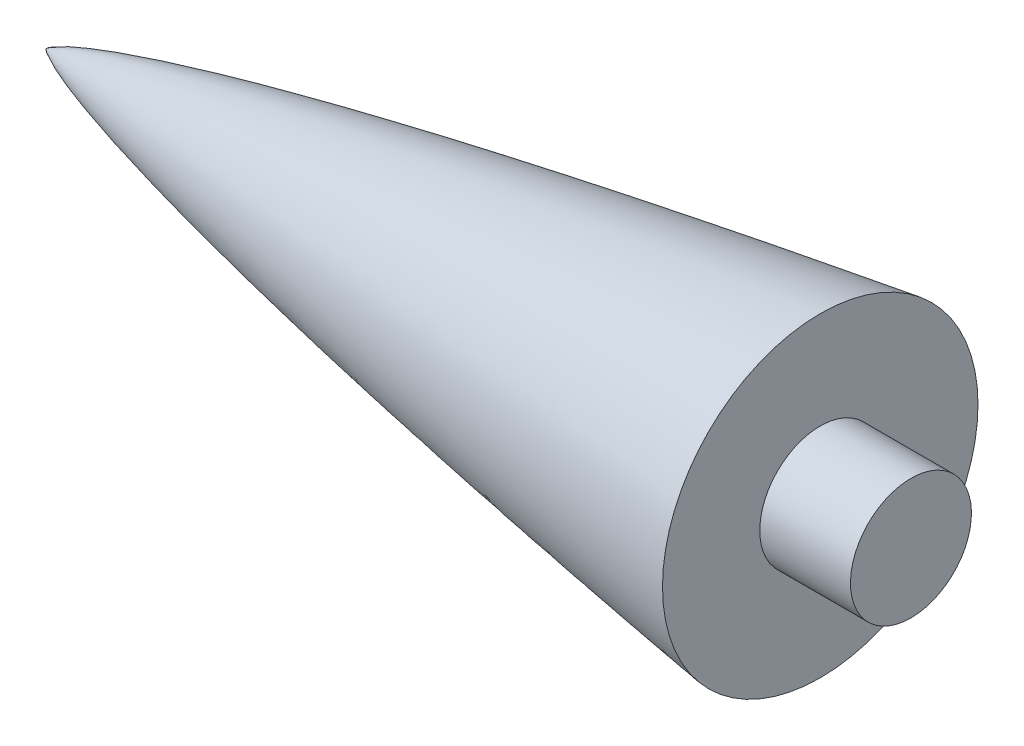
SolidWorks part; units mm, degrees
material "6061-T6 (SS)"
ref_plane "Front" through (0, 0, 0) normal (0, 0, 1) x (1, 0, 0)
ref_plane "Top" through (0, 0, 0) normal (0, 1, 0) x (1, 0, 0)
ref_plane "Right" through (0, 0, 0) normal (1, 0, 0) x (0, 0, -1)
sketch "Sketch7" plane through (0, 0, 0) normal (0, 0, 1) x (1, 0, 0)
  line L0 (0, 0) -> (1126.623, 0) construction
  line L1 (762, 83.8413) -> (762, 0)
  line L2 (0, 0) -> (762, 0)
  spline S0 degree 4 poles (0, 0) (0.0025, 0.0077) (0.0085, 0.0225) (0.0254, 0.0499) (0.0657, 0.1001) (0.1275, 0.1632) (0.2121, 0.2373) (0.3323, 0.3316) (0.4768, 0.4341) (0.6465, 0.5448) (0.8414, 0.663) (1.1269, 0.8263) (1.5727, 1.0629) (2.3354, 1.4323) (3.7109, 2.0298) (6.1546, 2.9698) (10.668, 4.4903) (18.9995, 6.9173) (33.3858, 10.5209) (58.2147, 15.8817) (92.5014, 22.2364) (134.3472, 29.0669) (181.2323, 35.9138) (228.1994, 42.1676) (275.2294, 47.9287) (322.3096, 53.2619) (369.4323, 58.2049) (416.5919, 62.7813) (463.7847, 67.0021) (511.0079, 70.8684) (558.2595, 74.3704) (605.5383, 77.4858) (646.9303, 79.8373) (682.4256, 81.5392) (710.8634, 82.6554) (729.8529, 83.259) (745.3094, 83.6328) (754.8465, 83.7859) (759.6154, 83.8349) (762, 83.8413) knots 0 0 0 0 0 0.000042 0.000084 0.000167 0.000334 0.000501 0.000668 0.000962 0.001257 0.001556 0.001855 0.002675 0.003884 0.005967 0.009662 0.016304 0.028676 0.05114 0.086868 0.148544 0.21022 0.271896 0.333573 0.395249 0.456925 0.518602 0.580278 0.641954 0.70363 0.765307 0.826983 0.888659 0.919497 0.950336 0.975168 0.987584 1 1 1 1 1 construction
  spline S1 degree 4 poles (0, 0) (0.0025, 0.0077) (0.0085, 0.0225) (0.0254, 0.0499) (0.0657, 0.1001) (0.1275, 0.1632) (0.2121, 0.2373) (0.3323, 0.3316) (0.4768, 0.4341) (0.6465, 0.5448) (0.8414, 0.663) (1.1269, 0.8263) (1.5727, 1.0629) (2.3354, 1.4323) (3.7109, 2.0298) (6.1546, 2.9698) (10.668, 4.4903) (18.9995, 6.9173) (33.3858, 10.5209) (58.2147, 15.8817) (92.5014, 22.2364) (134.3472, 29.0669) (181.2323, 35.9138) (228.1994, 42.1676) (275.2294, 47.9287) (322.3096, 53.2619) (369.4323, 58.2049) (416.5919, 62.7813) (463.7847, 67.0021) (511.0079, 70.8684) (558.2595, 74.3704) (605.5383, 77.4858) (646.9303, 79.8373) (682.4256, 81.5392) (710.8634, 82.6554) (729.8529, 83.259) (745.3094, 83.6328) (754.8465, 83.7859) (759.6154, 83.8349) (762, 83.8413) knots 0 0 0 0 0 0.000042 0.000084 0.000167 0.000334 0.000501 0.000668 0.000962 0.001257 0.001556 0.001855 0.002675 0.003884 0.005967 0.009662 0.016304 0.028676 0.05114 0.086868 0.148544 0.21022 0.271896 0.333573 0.395249 0.456925 0.518602 0.580278 0.641954 0.70363 0.765307 0.826983 0.888659 0.919497 0.950336 0.975168 0.987584 1 1 1 1 1
revolve "Revolve3" add sketch "Sketch7" angle 360 about L0
sketch "Sketch8" plane through (762, 0, 0) normal (1, 0, 0) x (0, 0, -1)
  circle A0 centre (0, 0) radius 83.8413 construction
  circle A1 centre (0, 0) radius 83.8413
extrude "Boss-Extrude1" add sketch "Sketch8" along normal blind 10.16
ref_plane "Plane1" through (162.56, 0, 0) normal (1, 0, 0) x (0, 0, -1)
sketch "Sketch9" plane through (162.56, 0, 0) normal (1, 0, 0) x (0, 0, -1)
  circle A0 centre (0, 0) radius 117.4613
extrude "Cut-Extrude1" cut sketch "Sketch9" along normal blind 681.99
sketch "Sketch10" plane through (162.56, 0, 0) normal (1, 0, 0) x (0, 0, -1)
  circle A0 centre (0, 0) radius 12.7
  dimension "D1" = 25.4
extrude "Boss-Extrude2" add sketch "Sketch10" along normal blind 19.05
cosmetic thread "Cosmetic Thread6" parameters "D2"=24.4
